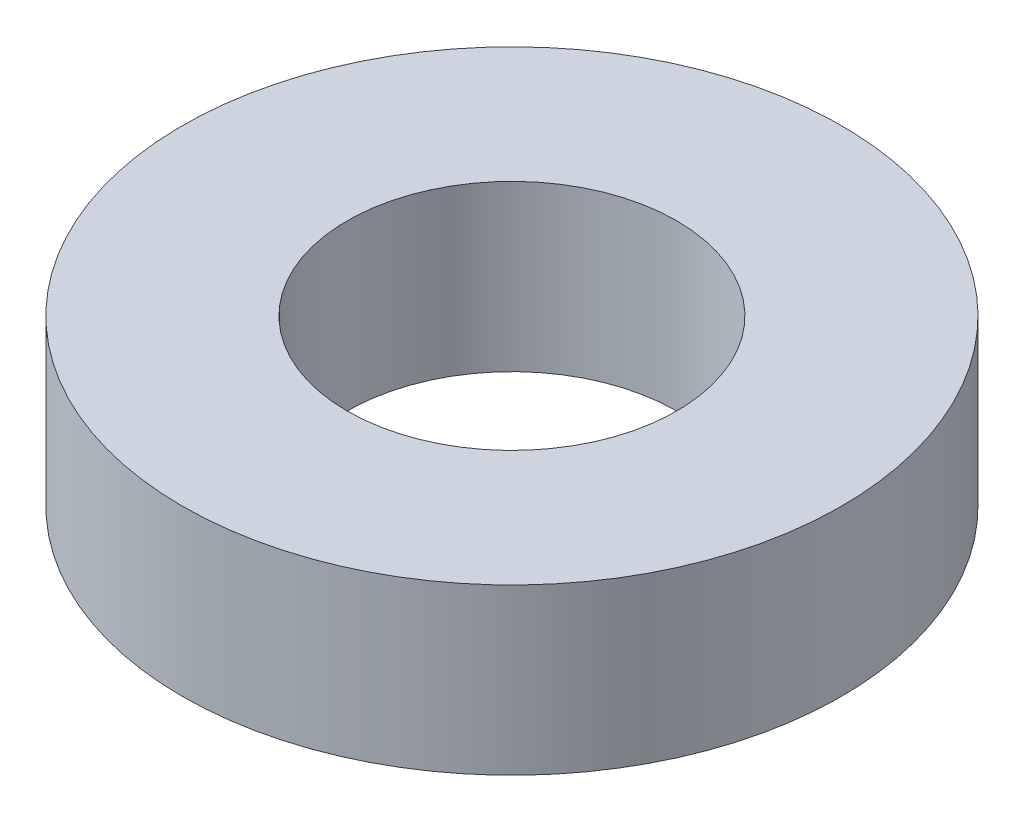
SolidWorks part; units mm, degrees
ref_plane "Front Plane" through (0, 0, 0) normal (0, 0, 1) x (1, 0, 0)
ref_plane "Top Plane" through (0, 0, 0) normal (0, 1, 0) x (1, 0, 0)
ref_plane "Right Plane" through (0, 0, 0) normal (1, 0, 0) x (0, 0, -1)
sketch "Sketch1" plane through (0, 0, 0) normal (0, 1, 0) x (1, 0, 0)
  circle A0 centre (0, 0) radius 25.4
  circle A1 centre (0, 0) radius 12.7
  dimension "D1" = 50.8
  dimension "D2" = 25.4
extrude "Boss-Extrude1" add sketch "Sketch1" along normal blind 12.7
